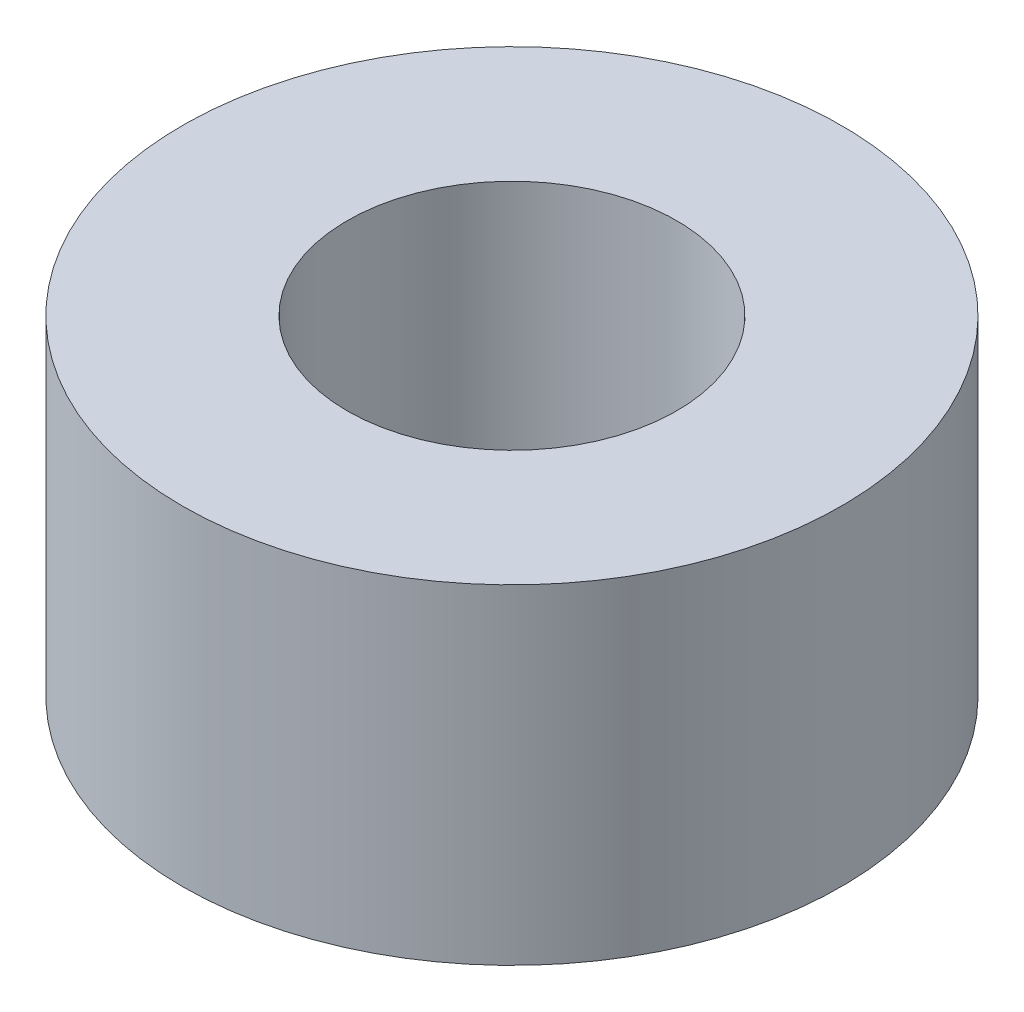
SolidWorks part; units mm, degrees
ref_plane "前视基准面" through (0, 0, 0) normal (0, 0, 1) x (1, 0, 0)
ref_plane "上视基准面" through (0, 0, 0) normal (0, 1, 0) x (1, 0, 0)
ref_plane "右视基准面" through (0, 0, 0) normal (1, 0, 0) x (0, 0, -1)
sketch "草图1" plane through (0, 0, 0) normal (0, 1, 0) x (1, 0, 0)
  circle A0 centre (0, 0) radius 3
  circle A1 centre (0, 0) radius 6
  dimension "D1" = 12
  dimension "D2" = 6
extrude "凸台-拉伸1" add sketch "草图1" along normal blind 6
